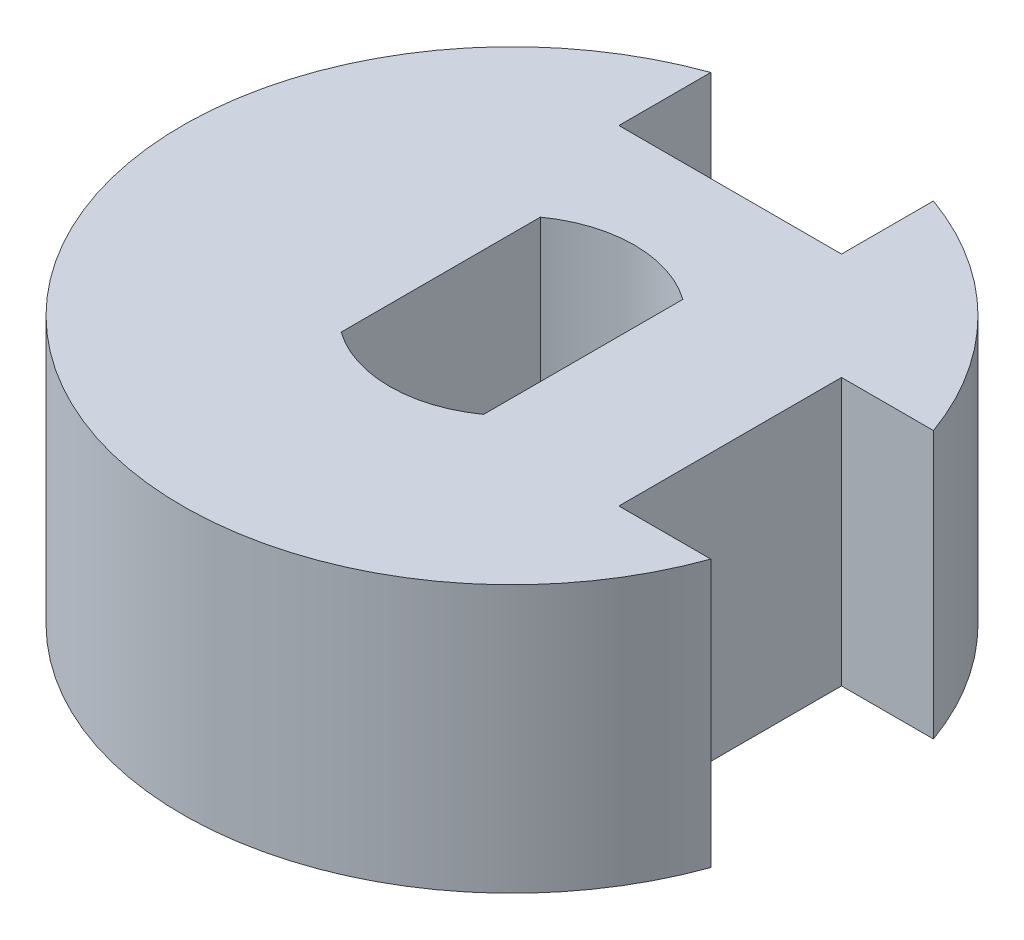
SolidWorks part; units mm, degrees
ref_plane "Front Plane" through (0, 0, 0) normal (0, 0, 1) x (1, 0, 0)
ref_plane "Top Plane" through (0, 0, 0) normal (0, 1, 0) x (1, 0, 0)
ref_plane "Right Plane" through (0, 0, 0) normal (1, 0, 0) x (0, 0, -1)
sketch "Sketch1" plane through (0, 0, 0) normal (0, 1, 0) x (1, 0, 0)
  line L0 (-1.6, 2.2366) -> (-1.6, -2.2366)
  line L1 (1.6, 2.2366) -> (1.6, -2.2366)
  line L3 (4.9, 2.5) -> (9.9, 2.5)
  line L4 (4.9, 2.5) -> (4.9, -2.5)
  line L5 (4.9, -2.5) -> (9.9, -2.5)
  line L6 (9.9, 2.5) -> (9.9, -2.5)
  line L7 (4.9, 2.5) -> (9.9, -2.5) construction
  line L8 (4.9, -2.5) -> (9.9, 2.5) construction
  line L9 (-2.5, 9.9) -> (2.5, 9.9)
  line L10 (-2.5, 9.9) -> (-2.5, 4.9)
  line L11 (-2.5, 4.9) -> (2.5, 4.9)
  line L12 (2.5, 9.9) -> (2.5, 4.9)
  line L13 (-2.5, 9.9) -> (2.5, 4.9) construction
  line L14 (-2.5, 4.9) -> (2.5, 9.9) construction
  circle A0 centre (0, 0) radius 7.4
  arc A1 (1.6, 2.2366) -> (-1.6, 2.2366) centre (0, 0) ccw
  arc A2 (-1.6, -2.2366) -> (1.6, -2.2366) centre (0, 0) ccw
  point P3 (7.4, 0)
  point P12 (0, 7.4)
  dimension "D1" = 14.8
  dimension "D2" = 5.5
  dimension "D3" = 3.2
  dimension "D4" = 1.6
  dimension "D5" = 5
  dimension "D6" = 2.5
  dimension "D7" = 5
  dimension "D8" = 5
extrude "Boss-Extrude1" add sketch "Sketch1" along normal blind 6 contours L3 A0 L12 L11 L10 L5 L4 A2 L0 A1 L1
